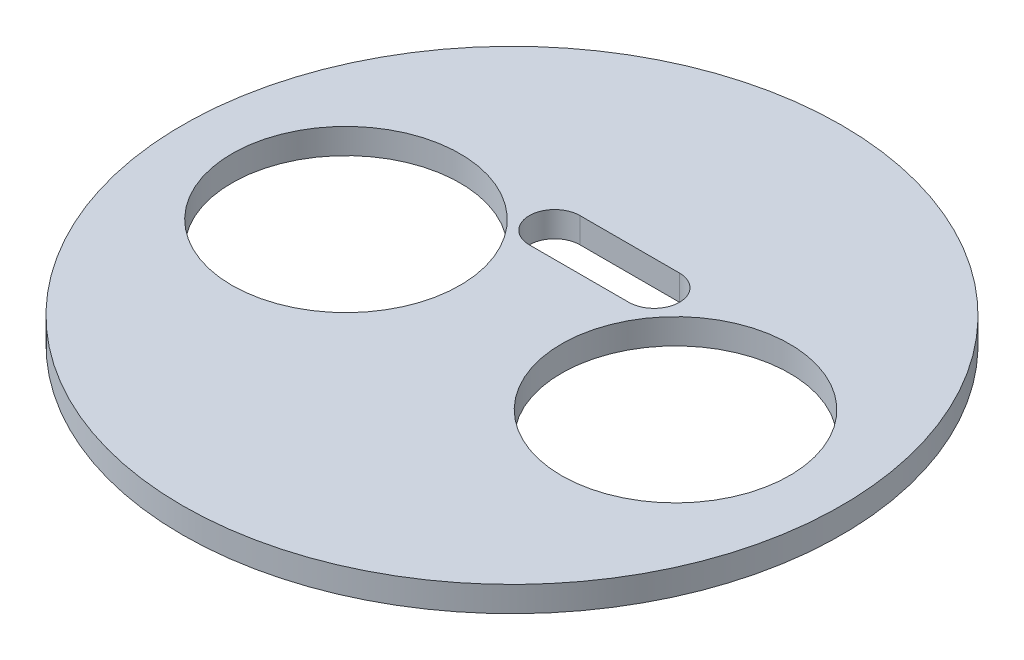
SolidWorks part; units mm, degrees
ref_plane "Front Plane" through (0, 0, 0) normal (0, 0, 1) x (1, 0, 0)
ref_plane "Top Plane" through (0, 0, 0) normal (0, 1, 0) x (1, 0, 0)
ref_plane "Right Plane" through (0, 0, 0) normal (1, 0, 0) x (0, 0, -1)
sketch "Sketch1" plane through (0, 0, 0) normal (0, 1, 0) x (1, 0, 0)
  line L2 (22.0572, 10.7978) -> (22.0874, 10.8113) construction
  line L4 (22.0572, -9.1753) -> (22.0874, -9.1887) construction
  line L11 (-22.9428, -9.1887) -> (-22.9126, -9.1887)
  line L15 (-22.9428, 10.8113) -> (-22.9126, 10.8113)
  line L16 (22.0572, -9.1887) -> (22.0572, -9.1753)
  line L17 (-4.4797, 10.3113) -> (3.3711, 10.3113)
  line L18 (-4.4797, 6.3113) -> (3.3711, 6.3113)
  line L34 (22.0572, 10.7978) -> (22.0572, 10.8113)
  circle A29 centre (-0.3444, 0.8113) radius 26
  circle A30 centre (12.5572, 0.8113) radius 9
  circle A31 centre (-13.4428, 0.8113) radius 9
  arc A34 (-4.4797, 10.3113) -> (-4.4797, 6.3113) centre (-4.4797, 8.3113) ccw
  arc A35 (3.3711, 6.3113) -> (3.3711, 10.3113) centre (3.3711, 8.3113) ccw
  point P1 (0, 0)
  point P19 (-0.5543, 8.3113)
  point P26 (-0.5543, 8.3113)
  dimension "D8" = 18
  dimension "D9" = 18
  dimension "D16" = 2
  dimension "D1" = 45
  dimension "D2" = 20
  dimension "D5" = 45
  dimension "D6" = 20
  dimension "D7" = 26
  dimension "D22" = 2.5
extrude "Boss-Extrude1" add sketch "Sketch1" along normal blind 2
